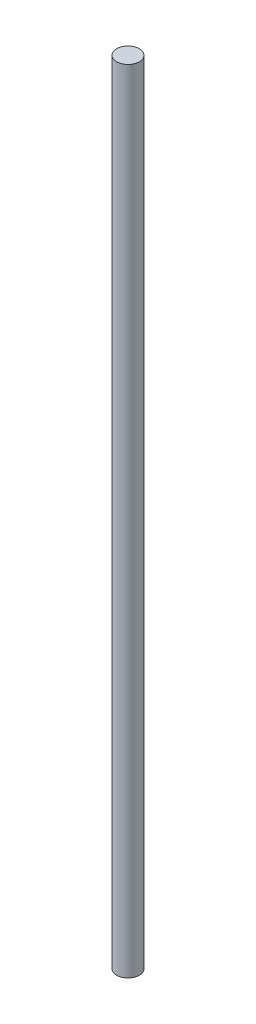
SolidWorks part; units mm, degrees
ref_plane "Front Plane" through (0, 0, 0) normal (0, 0, 1) x (1, 0, 0)
ref_plane "Top Plane" through (0, 0, 0) normal (0, 1, 0) x (1, 0, 0)
ref_plane "Right Plane" through (0, 0, 0) normal (1, 0, 0) x (0, 0, -1)
sketch "Sketch1" plane through (0, 0, 0) normal (0, 1, 0) x (1, 0, 0)
  circle A0 centre (0, 0) radius 6
  dimension "D1" = 12
extrude "Boss-Extrude1" add sketch "Sketch1" along normal blind 420
equation "\"d\"= 12"
equation "\"l\"= 420"
equation "\"D1@Boss-Extrude1\"= \"l\""
equation "\"D1@Sketch1\"=\"d\""
